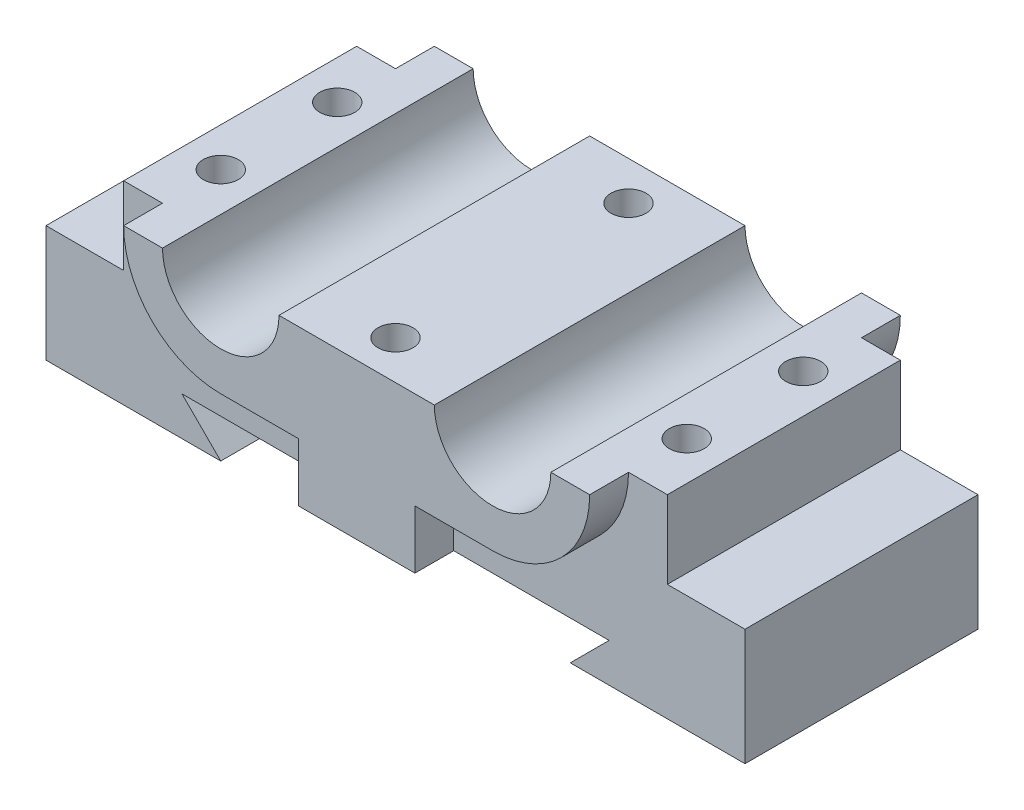
SolidWorks part; units mm, degrees
ref_plane "Front Plane" through (0, 0, 0) normal (0, 0, 1) x (1, 0, 0)
ref_plane "Top Plane" through (0, 0, 0) normal (0, 1, 0) x (1, 0, 0)
ref_plane "Right Plane" through (0, 0, 0) normal (1, 0, 0) x (0, 0, -1)
sketch "Sketch1" plane through (0, 0, 0) normal (0, 0, 1) x (1, 0, 0)
  line L0 (0, 0) -> (0, 15)
  line L1 (0, 15) -> (10, 15)
  line L2 (10, 15) -> (10, 25)
  line L3 (10, 25) -> (80, 25)
  line L4 (80, 25) -> (80, 15)
  line L5 (80, 15) -> (90, 15)
  line L6 (90, 15) -> (90, 0)
  line L7 (90, 0) -> (67.5, 0)
  line L8 (67.5, 0) -> (72.5, 5)
  line L9 (72.5, 5) -> (17.5, 5)
  line L10 (17.5, 5) -> (22.5, 0)
  line L11 (22.5, 0) -> (0, 0)
  point P3 (45, 5)
  point P14 (45, 25)
  dimension "D1" = 15
  dimension "D2" = 10
  dimension "D3" = 5
  dimension "D4" = 45
  dimension "D5" = 5
  dimension "D6" = 22.5
  dimension "D7" = 22.5
  dimension "D8" = 70
extrude "Boss-Extrude1" add sketch "Sketch1" along normal blind 30
ref_plane "Plane1" through (0, 0, -5) normal (0, 0, 1) x (1, 0, 0)
sketch "Sketch3" plane through (0, 0, -5) normal (0, 0, 1) x (1, 0, 0)
  line L0 (45, 5) -> (52.5, 5)
  line L1 (17.5, 5) -> (72.5, 5) construction
  line L2 (52.5, 5) -> (52.5, 12.5)
  line L3 (52.5, 12.5) -> (62.5, 12.5)
  line L4 (80, 25) -> (10, 25) construction
  line L5 (75, 25) -> (15, 25)
  line L6 (45, 5) -> (37.5, 5)
  line L7 (37.5, 5) -> (37.5, 12.5)
  line L8 (37.5, 12.5) -> (27.5, 12.5)
  line L9 (80, 15) -> (80, 25) construction
  arc A0 (62.5, 12.5) -> (75, 25) centre (62.5, 25) ccw
  arc A1 (27.5, 12.5) -> (15, 25) centre (27.5, 25) cw
  dimension "D3" = 12.5
  dimension "D4" = 12.5
  dimension "D1" = 15
  dimension "D2" = 7.5
  dimension "D5" = 35
  dimension "D6" = 17.5
extrude "Boss-Extrude2" add sketch "Sketch3" along normal blind 40
sketch "Sketch4" plane through (0, 0, -5) normal (0, 0, 1) x (1, 0, 0)
  circle A0 centre (27.5, 25) radius 7.5
  circle A1 centre (62.5, 25) radius 7.5
  dimension "D1" = 15
  dimension "D2" = 15
extrude "Cut-Extrude1" cut sketch "Sketch4" along normal blind 40
ref_plane "Plane2" through (0, 25, 0) normal (0, 1, 0) x (1, 0, 0)
sketch "Sketch5" plane through (0, 25, 0) normal (0, 1, 0) x (1, 0, 0)
  line L0 (15, -30) -> (10, -30) construction
  line L1 (10, -30) -> (10, 0) construction
  line L2 (80, -30) -> (80, 0) construction
  line L3 (15, 0) -> (15, 5) construction
  line L4 (55, -35) -> (35, -35) construction
  line L7 (10, -30) -> (10, 0) construction
  line L8 (80, -30) -> (80, 0) construction
  circle A0 centre (15, -7.5) radius 2.25
  circle A1 centre (15, -22.5) radius 2.25
  circle A2 centre (45, 0) radius 2.25
  circle A3 centre (45, -30) radius 2.25
  circle A4 centre (75, -7.5) radius 2.25
  circle A5 centre (75, -22.5) radius 2.25
  dimension "D1" = 4.5
  dimension "D2" = 15
  dimension "D3" = 7.5
  dimension "D4" = 5
  dimension "D5" = 5
  dimension "D6" = 30
  dimension "D7" = 30
  dimension "D8" = 5
  dimension "D9" = 5
  dimension "D10" = 5
extrude "Cut-Extrude2" cut sketch "Sketch5" against normal blind 15
